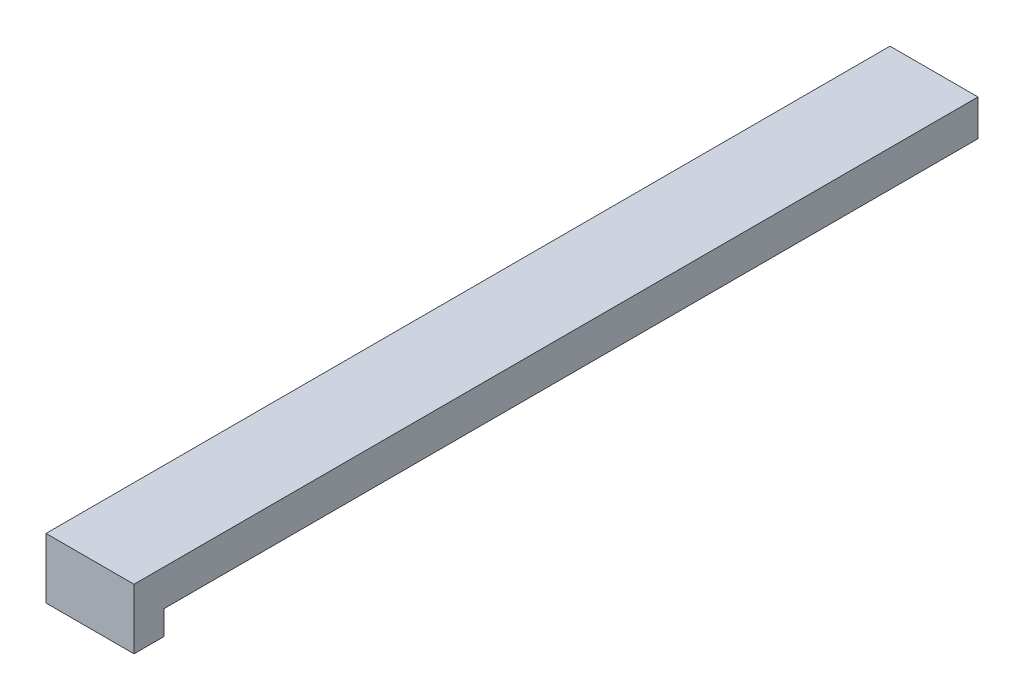
SolidWorks part; units mm, degrees
ref_plane "Plan de face" through (0, 0, 0) normal (0, 0, 1) x (1, 0, 0)
ref_plane "Plan de dessus" through (0, 0, 0) normal (0, 1, 0) x (1, 0, 0)
ref_plane "Plan de droite" through (0, 0, 0) normal (1, 0, 0) x (0, 0, -1)
sketch "Esquisse1" plane through (0, 0, 0) normal (0, 0, 1) x (1, 0, 0)
  line L0 (-7.3, 0) -> (-7.3, -6)
  line L1 (-7.3, -6) -> (-4.3, -6)
  line L2 (-4.3, -6) -> (-4.3, -2)
  line L3 (-4.3, -2) -> (4.3, -2)
  line L4 (4.3, -2) -> (4.3, -6)
  line L5 (4.3, -6) -> (7.3, -6)
  line L6 (7.3, -6) -> (7.3, 0)
  line L7 (7.3, 0) -> (-7.3, 0)
  point P9 (0, 0)
  dimension "D1" = 3
  dimension "D2" = 3
  dimension "D3" = 14.6
  dimension "D4" = 4
  dimension "D5" = 4
  dimension "D6" = 6
extrude "Boss.-Extru.4" add sketch "Esquisse1" along normal blind 140
sketch "Esquisse2" plane through (0, -6, 0) normal (0, -1, 0) x (1, 0, 0)
  line L0 (7.3, 140) -> (7.3, 0) construction
  line L1 (-7.3, 0) -> (7.3, 0)
  line L2 (-7.3, 0) -> (-7.3, 5)
  line L3 (-7.3, 5) -> (7.3, 5)
  line L4 (7.3, 0) -> (7.3, 5)
  dimension "D1" = 5
extrude "Boss.-Extru.5" add sketch "Esquisse2" against normal through all
sketch "Esquisse4" plane through (0, 0, 0) normal (0, 1, 0) x (1, 0, 0)
  line L0 (7.3, -140) -> (7.3, 0) construction
  line L1 (-7.3, -140) -> (7.3, -140)
  line L2 (-7.3, -140) -> (-7.3, -135)
  line L3 (-7.3, -135) -> (7.3, -135)
  line L4 (7.3, -140) -> (7.3, -135)
  dimension "D1" = 5
extrude "Boss.-Extru.6" add sketch "Esquisse4" against normal blind 10
